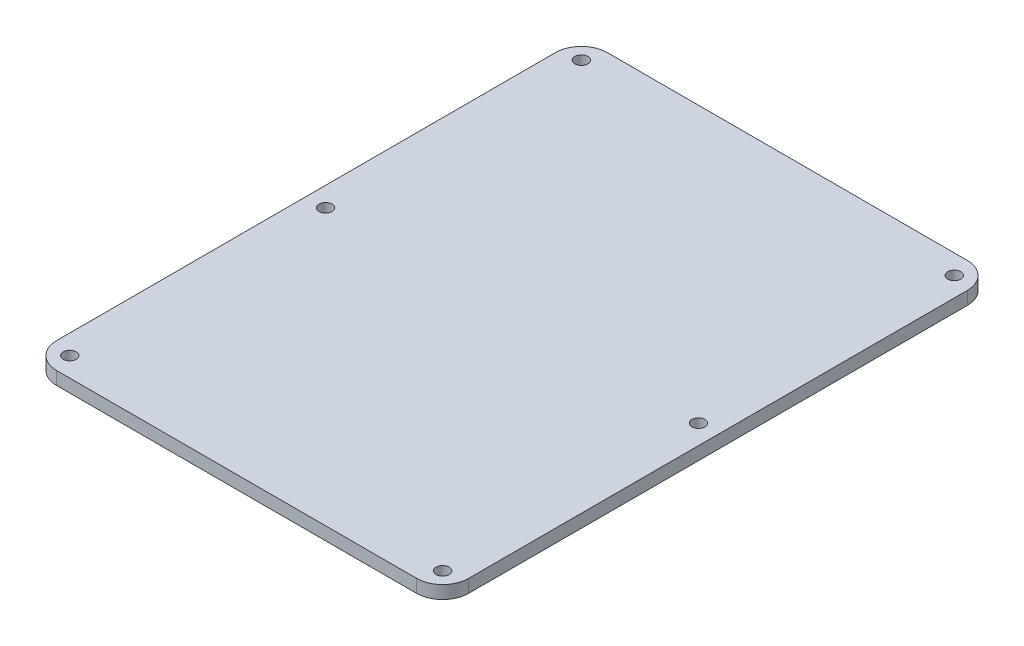
SolidWorks part; units mm, degrees
ref_plane "Front" through (0, 0, 0) normal (0, 0, 1) x (1, 0, 0)
ref_plane "Top" through (0, 0, 0) normal (0, 1, 0) x (1, 0, 0)
ref_plane "Right" through (0, 0, 0) normal (1, 0, 0) x (0, 0, -1)
sketch "Sketch1" plane through (0, 0, 0) normal (0, 1, 0) x (1, 0, 0)
  line L1 (-47.5, -63.5) -> (47.5, -63.5)
  line L2 (-47.5, -63.5) -> (-47.5, 63.5)
  line L3 (-47.5, 63.5) -> (47.5, 63.5)
  line L4 (47.5, -63.5) -> (47.5, 63.5)
  line L5 (-47.5, -63.5) -> (47.5, 63.5) construction
  line L6 (-47.5, 63.5) -> (47.5, -63.5) construction
  point P0 (0, 0)
  dimension "D1" = 95
  dimension "D2" = 127
extrude "Boss-Extrude1" add sketch "Sketch1" along normal blind 3
fillet "Fillet1" radius 6 4 edges at (47.5, 1.5, -63.5) (-47.5, 1.5, -63.5) (-47.5, 1.5, 63.5) (47.5, 1.5, 63.5)
sketch "Sketch2" plane through (0, 3, 0) normal (0, 1, 0) x (1, 0, 0)
  line L2 (41.5, 63.5) -> (-41.5, 63.5) construction
  line L3 (-47.5, 57.5) -> (-47.5, -57.5) construction
  circle A0 centre (-43, 59) radius 1.5
  dimension "D1" = 4.5
  dimension "D3" = 3
  dimension "D2" = 4.5
extrude "Cut-Extrude1" cut sketch "Sketch2" against normal through all
mirror "Mirror1" about plane through (0, 0, 0) normal (0, 0, 1) of "Cut-Extrude1"
pattern_linear "LPattern2" count 2 spacing 59 along (0, 0, 1) of "Cut-Extrude1"
mirror "Mirror2" about plane through (0, 0, 0) normal (1, 0, 0) of "LPattern2", "Mirror1", "Cut-Extrude1"
